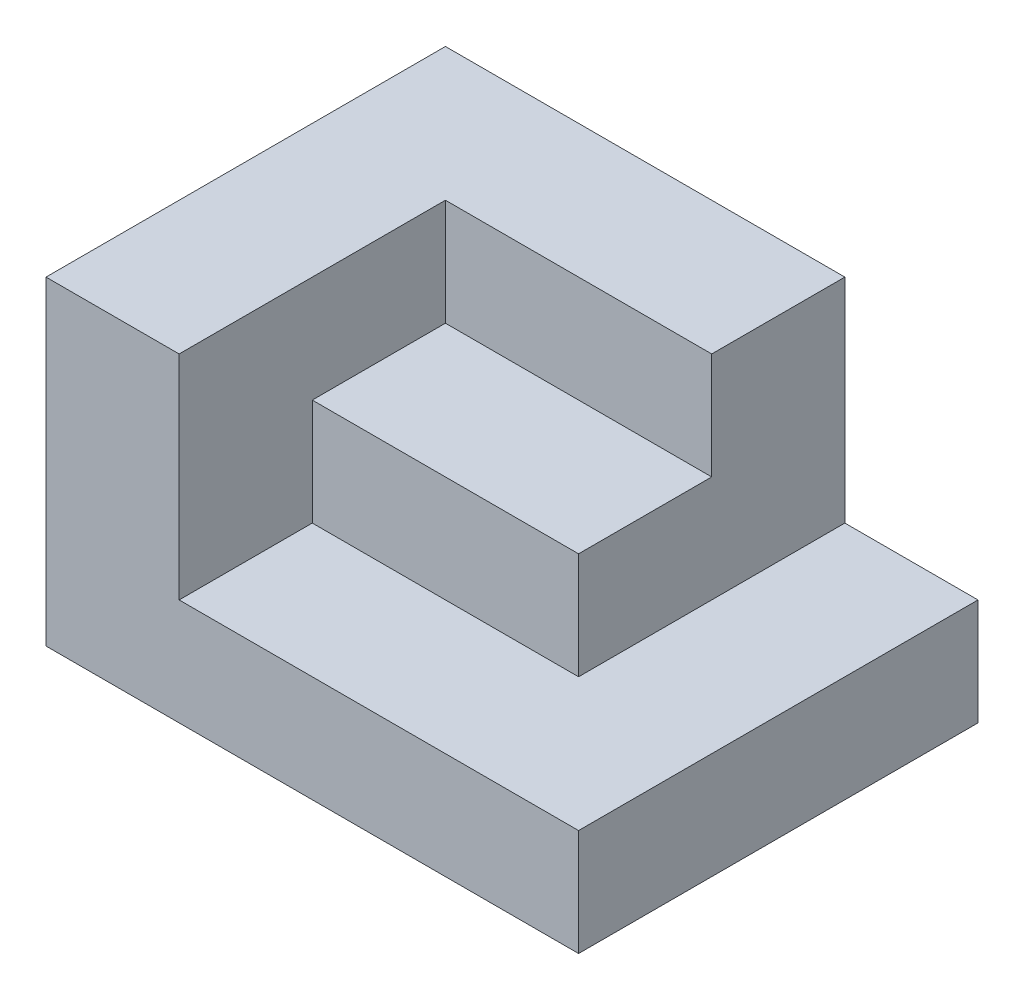
SolidWorks part; units mm, degrees
ref_plane "Front Plane" through (0, 0, 0) normal (0, 0, 1) x (1, 0, 0)
ref_plane "Top Plane" through (0, 0, 0) normal (0, 1, 0) x (1, 0, 0)
ref_plane "Right Plane" through (0, 0, 0) normal (1, 0, 0) x (0, 0, -1)
sketch "Sketch1" plane through (0, 0, 0) normal (0, 1, 0) x (1, 0, 0)
  line L1 (-50, -37.5) -> (50, -37.5)
  line L2 (-50, -37.5) -> (-50, 37.5)
  line L3 (-50, 37.5) -> (50, 37.5)
  line L4 (50, -37.5) -> (50, 37.5)
  line L5 (-50, -37.5) -> (50, 37.5) construction
  line L6 (-50, 37.5) -> (50, -37.5) construction
  point P0 (0, 0)
  dimension "D1" = 100
  dimension "D2" = 75
extrude "Boss-Extrude1" add sketch "Sketch1" along normal blind 60
sketch "Sketch2" plane through (0, 60, 0) normal (0, 1, 0) x (1, 0, 0)
  line L0 (-25, -37.5) -> (-25, -12.5)
  line L1 (-50, -37.5) -> (50, -37.5) construction
  line L2 (-25, -12.5) -> (25, -12.5)
  line L3 (25, -12.5) -> (25, 37.5)
  line L4 (50, 37.5) -> (-50, 37.5) construction
  line L5 (-50, 37.5) -> (-50, -37.5) construction
  dimension "D1" = 25
  dimension "D2" = 75
  dimension "D3" = 50
extrude "Cut-Extrude1" cut sketch "Sketch2" against normal blind 40 and the other way through all flip side to cut
sketch "Sketch3" plane through (0, 60, 0) normal (0, 1, 0) x (1, 0, 0)
  line L0 (-25, -12.5) -> (-25, 12.5)
  line L1 (-25, 12.5) -> (25, 12.5)
  line L2 (25, 12.5) -> (25, 37.5)
  line L3 (25, 37.5) -> (-50, 37.5) construction
  line L4 (-50, 37.5) -> (-50, -37.5) construction
  dimension "D1" = 25
  dimension "D2" = 75
extrude "Cut-Extrude2" cut sketch "Sketch3" against normal blind 20 and the other way through all flip side to cut
